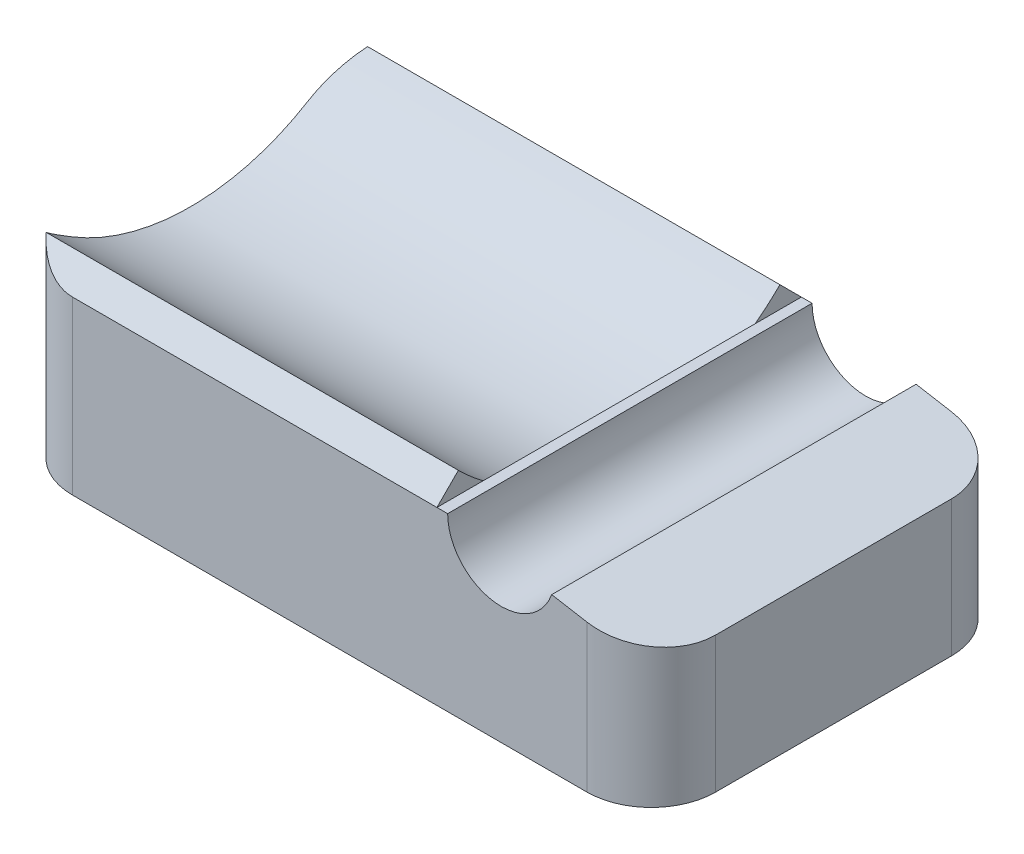
SolidWorks part; units mm, degrees
ref_plane "Front Plane" through (0, 0, 0) normal (0, 0, 1) x (1, 0, 0)
ref_plane "Top Plane" through (0, 0, 0) normal (0, 1, 0) x (1, 0, 0)
ref_plane "Right Plane" through (0, 0, 0) normal (1, 0, 0) x (0, 0, -1)
sketch "Sketch1" plane through (0, 0, 0) normal (0, 1, 0) x (1, 0, 0)
  line L1 (0, 0) -> (60, 0)
  line L2 (0, 0) -> (0, 34)
  line L3 (0, 34) -> (60, 34)
  line L4 (60, 0) -> (60, 34)
  dimension "D1" = 34
  dimension "D2" = 60
extrude "Boss-Extrude1" add sketch "Sketch1" along normal blind 16
sketch "Sketch3" plane through (0, 0, 0) normal (-1, 0, 0) x (0, 0, 1)
  line L0 (-34, 16) -> (-32, 18)
  line L1 (-2, 18) -> (0, 16)
  line L2 (0, 16) -> (0, 0) construction
  line L3 (-34, 16) -> (0, 16) construction
  line L4 (-34, 16) -> (-29.6886, 16)
  line L5 (0, 16) -> (-4.3114, 16)
  arc A0 (-32, 18) -> (-29.6886, 16) centre (-17, 33) ccw
  arc A1 (-4.3114, 16) -> (-2, 18) centre (-17, 33) ccw
  dimension "D1" = 45
  dimension "D2" = 45
  dimension "D3" = 2
extrude "Boss-Extrude2" add sketch "Sketch3" against normal blind 40
sketch "Sketch4" plane through (0, 0, 0) normal (-1, 0, 0) x (0, 0, 1)
  line L0 (-19.4721, 33) -> (-38.2132, 33)
  line L1 (4.2132, 33) -> (-19.4721, 33)
  arc A0 (-38.2132, 33) -> (4.2132, 33) centre (-17, 33) ccw
  arc A1 (-32, 18) -> (-29.6886, 16) centre (-17, 33) ccw construction
extrude "Cut-Extrude2" cut sketch "Sketch4" against normal up to surface (40 mm away) up to face at (40, 16.6528, -31.9082)
sketch "Sketch2" plane through (0, 0, 0) normal (0, 0, 1) x (1, 0, 0)
  line L0 (40, 16) -> (60, 16) construction
  line L1 (0, 16) -> (0, 0) construction
  circle A0 centre (46, 16) radius 5
  dimension "D1" = 10
  dimension "D2" = 46
extrude "Cut-Extrude1" cut sketch "Sketch2" against normal through all
fillet "Fillet1" radius 6 4 edges at (0, 8, -34) (60, 8, -34) (60, 8, 0) (0, 8, 0)
sketch "Sketch5" plane through (0, 0, 0) normal (0, 0, 1) x (1, 0, 0)
  line L0 (50.7059, 14.3105) -> (60, 12.6927)
  line L1 (60, 16) -> (60, 0) construction
  line L2 (60, 12.6927) -> (60, 16)
  line L3 (60, 16) -> (51, 16)
  line L4 (51, 16) -> (50.7059, 14.3105)
  arc A0 (41, 16) -> (51, 16) centre (46, 16) ccw construction
extrude "Cut-Extrude3" cut sketch "Sketch5" against normal through all
